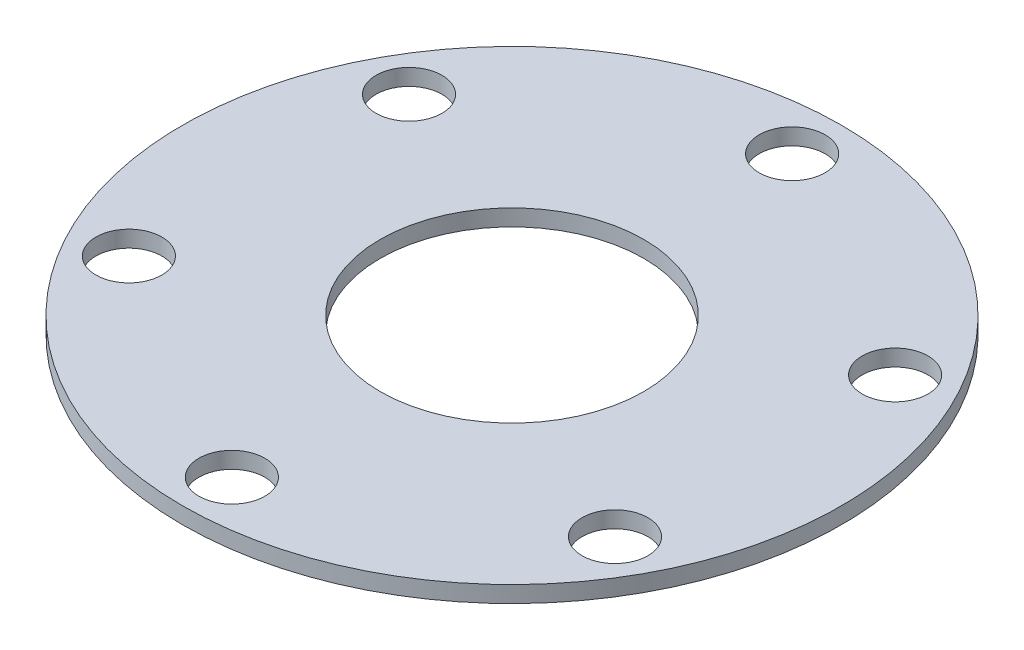
SolidWorks part; units mm, degrees
ref_plane "Front Plane" through (0, 0, 0) normal (0, 0, 1) x (1, 0, 0)
ref_plane "Top Plane" through (0, 0, 0) normal (0, 1, 0) x (1, 0, 0)
ref_plane "Right Plane" through (0, 0, 0) normal (1, 0, 0) x (0, 0, -1)
sketch "Sketch1" plane through (0, 0, 0) normal (0, 1, 0) x (1, 0, 0)
  circle A0 centre (0, 0) radius 127
extrude "Boss-Extrude1" add sketch "Sketch1" along normal blind 6.35
sketch "Sketch2" plane through (0, 6.35, 0) normal (0, 1, 0) x (1, 0, 0)
  circle A0 centre (0, 0) radius 50.8
extrude "Cut-Extrude1" cut sketch "Sketch2" against normal blind 6.35
sketch "Sketch3" plane through (0, 6.35, 0) normal (0, 1, 0) x (1, 0, 0)
  circle A0 centre (0, 107.95) radius 12.7
  circle A1 centre (93.6625, 53.975) radius 12.7
  circle A2 centre (93.6625, -53.975) radius 12.7
  circle A3 centre (0, -107.95) radius 12.7
  circle A4 centre (-93.6625, -53.975) radius 12.7
  circle A5 centre (-93.6625, 53.975) radius 12.7
  dimension "D1" = 53.975
  dimension "D2" = 53.975
  dimension "D3" = 53.975
  dimension "D4" = 53.975
  dimension "D5" = 107.95
  dimension "D7" = 25.4
  dimension "D8" = 93.6625
  dimension "D10" = 93.6625
  dimension "D6" = 107.95
  dimension "D9" = 93.6625
  dimension "D11" = 93.6625
sketch "Sketch4" plane through (0, 6.35, 0) normal (0, 1, 0) x (1, 0, 0)
  circle A0 centre (0, 107.95) radius 12.7
  circle A1 centre (93.6625, 53.975) radius 12.7
  circle A2 centre (0, -107.95) radius 12.7
  circle A3 centre (-93.6625, 53.975) radius 12.7
  circle A4 centre (-93.6625, -53.975) radius 12.7
  circle A5 centre (93.6625, -53.975) radius 12.7
  dimension "D1" = 107.95
  dimension "D2" = 107.95
  dimension "D3" = 53.975
  dimension "D4" = 53.975
  dimension "D5" = 53.975
  dimension "D6" = 53.975
  dimension "D7" = 93.6625
  dimension "D8" = 93.6625
  dimension "D9" = 93.6625
  dimension "D10" = 93.6625
extrude "Cut-Extrude4" cut sketch "Sketch4" against normal blind 12.7
